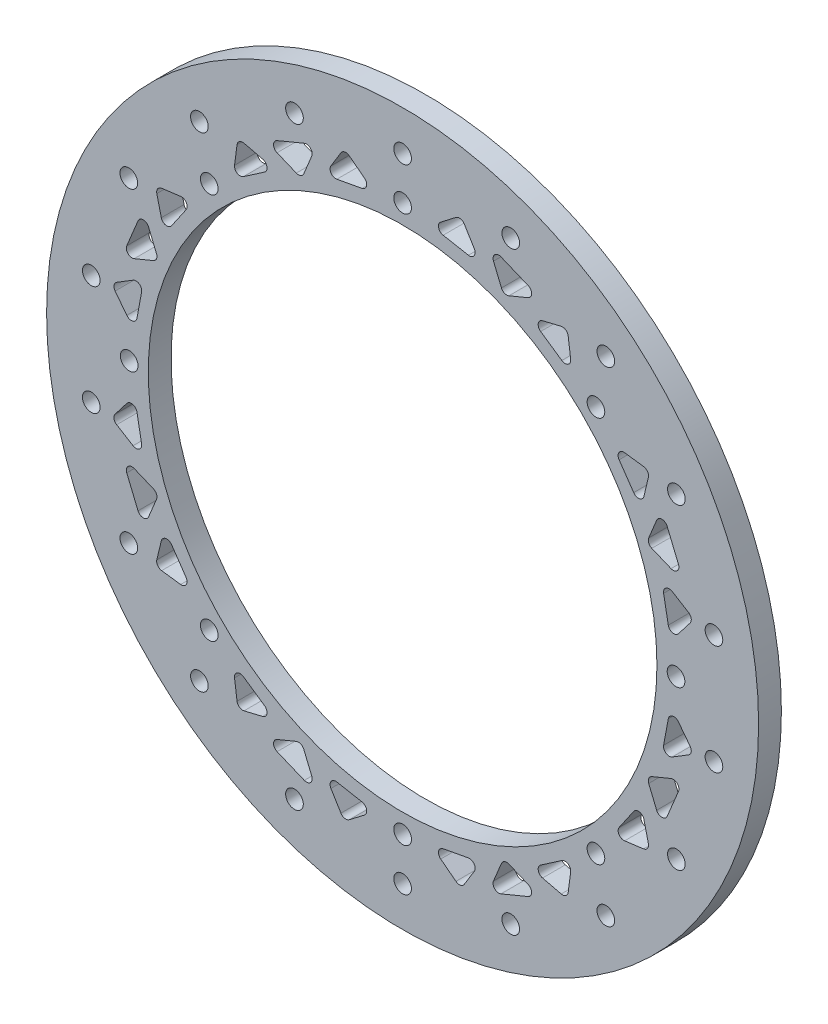
SolidWorks part; units mm, degrees
material "Thornel Mat VMA"
ref_plane "前视基准面" through (0, 0, 0) normal (0, 0, 1) x (1, 0, 0)
ref_plane "上视基准面" through (0, 0, 0) normal (0, 1, 0) x (1, 0, 0)
ref_plane "右视基准面" through (0, 0, 0) normal (1, 0, 0) x (0, 0, -1)
sketch "草图1" plane through (0, 0, 0) normal (0, 0, 1) x (1, 0, 0)
  circle A0 centre (0, 0) radius 62.5
  circle A1 centre (0, 0) radius 44.65
  dimension "D1" = 125
  dimension "D2" = 89.3
extrude "凸台-拉伸1" add sketch "草图1" along normal blind 4
sketch "草图2" plane through (0, 0, 4) normal (0, 0, 1) x (1, 0, 0)
  circle A0 centre (0, 55.5) radius 1.55
  dimension "D1" = 3.1
  dimension "D2" = 55.5
extrude "切除-拉伸1" cut sketch "草图2" against normal blind 4
pattern_circular "阵列(圆周)1" count 18 over 360 about axis through (0, 0, 0) along (0, 0, 1) of "切除-拉伸1"
sketch "草图3" plane through (0, 0, 4) normal (0, 0, 1) x (1, 0, 0)
  line L0 (-48, 0) -> (0, 0) construction
  circle A0 centre (-48, 0) radius 1.55
  dimension "D2" = 3.1
  dimension "D1" = 48
extrude "切除-拉伸2" cut sketch "草图3" against normal blind 4
pattern_circular "阵列(圆周)2" count 8 over 360 about axis through (0, 0, 0) along (0, 0, 1) of "切除-拉伸2"
sketch "草图4" plane through (0, 0, 4) normal (0, 0, 1) x (1, 0, 0)
  line L0 (0, 0) -> (-33.9411, -33.9411) construction
  line L1 (0, 0) -> (0, -48) construction
  line L2 (-33.9411, -33.9411) -> (0, -48) construction
  line L3 (-28.9212, -43.4092) -> (-29.7977, -36.7398)
  line L4 (-29.7977, -36.7398) -> (-22.3806, -41.8374)
  line L5 (-22.3806, -41.8374) -> (-28.9212, -43.4092)
  line L6 (0, 0) -> (-16.9706, -40.9706) construction
  line L7 (-4.9088, -47.0491) -> (-13.758, -45.409)
  line L8 (-13.758, -45.409) -> (-10.2446, -51.1453)
  line L9 (-10.2446, -51.1453) -> (-4.9088, -47.0491)
  line L10 (-24.2687, -45.5243) -> (-15.0299, -49.3511)
  line L11 (-15.0299, -49.3511) -> (-17.7359, -42.8183)
  line L12 (-17.7359, -42.8183) -> (-24.2687, -45.5243)
  dimension "D1" = 12
  dimension "D2" = 5
  dimension "D3" = 9
  dimension "D4" = 5
  dimension "D5" = 10
  dimension "D6" = 5
  dimension "D7" = 7
  dimension "D8" = 1
extrude "切除-拉伸3" cut sketch "草图4" against normal blind 4 contours L5 L4 L3 | L11 L12 L10 | L8 L9 L7
fillet "圆角1" radius 1 9 edges at (-4.9088, -47.0491, 2) (-10.2446, -51.1453, 2) (-13.758, -45.409, 2) (-15.0299, -49.3511, 2) (-24.2687, -45.5243, 2) (-17.7359, -42.8183, 2) (-22.3806, -41.8374, 2) (-28.9212, -43.4092, 2) (-29.7977, -36.7398, 2)
pattern_circular "阵列(圆周)3" count 8 over 360 about axis through (0, 0, 0) along (0, 0, 1) of "切除-拉伸3", "圆角1"
